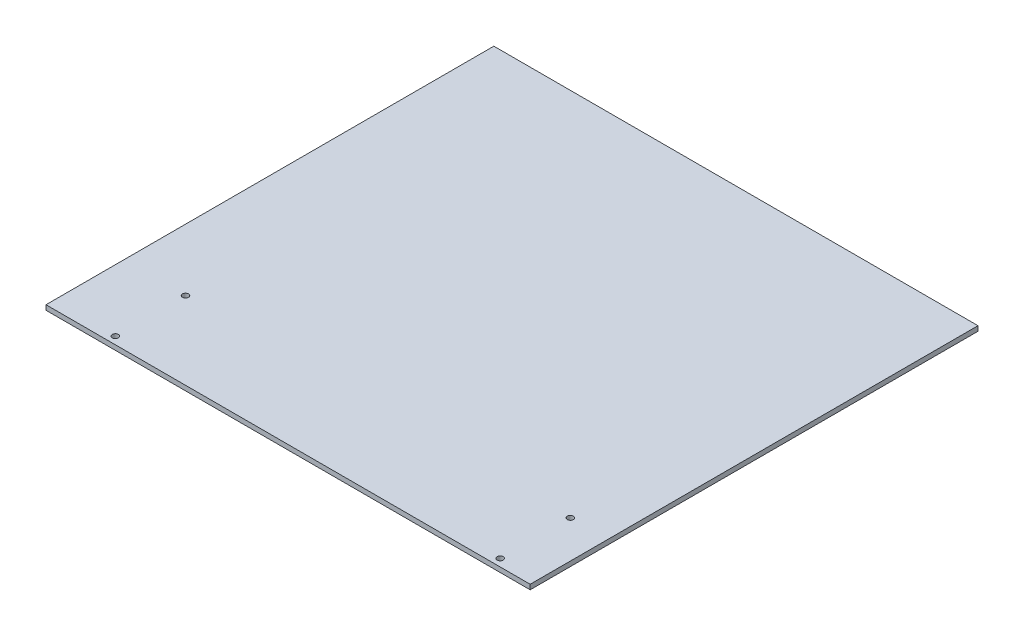
SolidWorks part; units mm, degrees
ref_plane "Front" through (0, 0, 0) normal (0, 0, 1) x (1, 0, 0)
ref_plane "Top" through (0, 0, 0) normal (0, 1, 0) x (1, 0, 0)
ref_plane "Right" through (0, 0, 0) normal (1, 0, 0) x (0, 0, -1)
sketch "草图1" plane through (0, 0, 0) normal (0, 1, 0) x (1, 0, 0)
  line L1 (-100, -92.5) -> (100, -92.5)
  line L2 (-100, -92.5) -> (-100, 92.5)
  line L3 (-100, 92.5) -> (100, 92.5)
  line L4 (100, -92.5) -> (100, 92.5)
  line L5 (-100, -92.5) -> (100, 92.5) construction
  line L6 (-100, 92.5) -> (100, -92.5) construction
  point P0 (0, 0)
  dimension "D1" = 200
  dimension "D2" = 185
extrude "凸台-拉伸1" add sketch "草图1" along normal blind 2
hole_wizard "大小mm 暗销槽口" positions "草图2" profile "草图3" size "Ø2.5" standard "ISO" slot yes
sketch "草图2" plane through (-57.3394, 0, -271.3993) normal (0, -1, 0) x (-1, 0, 0)
  point P0 (-141.8886, -331.8315)
  point P2 (-141.8886, -360.8321)
  point P4 (17.1062, -360.8321)
  point P6 (17.1062, -331.8315)
sketch "草图3" plane through (84.5491, 0, 60.4322) normal (1, 0, 0) x (0, 0, -1)
  line L0 (0, 0) -> (0, 2.7511)
  line L1 (0, 2.7511) -> (1.25, 2)
  line L2 (1.25, 2) -> (1.25, 0)
  line L3 (1.25, 0) -> (0, 0)
  line L4 (0, 2.7511) -> (-1.25, 2) construction
  line L5 (0, -6.35) -> (0, 107.95) construction
  dimension "孔直径" = 2.5
  dimension "孔深度" = 2
  dimension "导头角度" = 118
